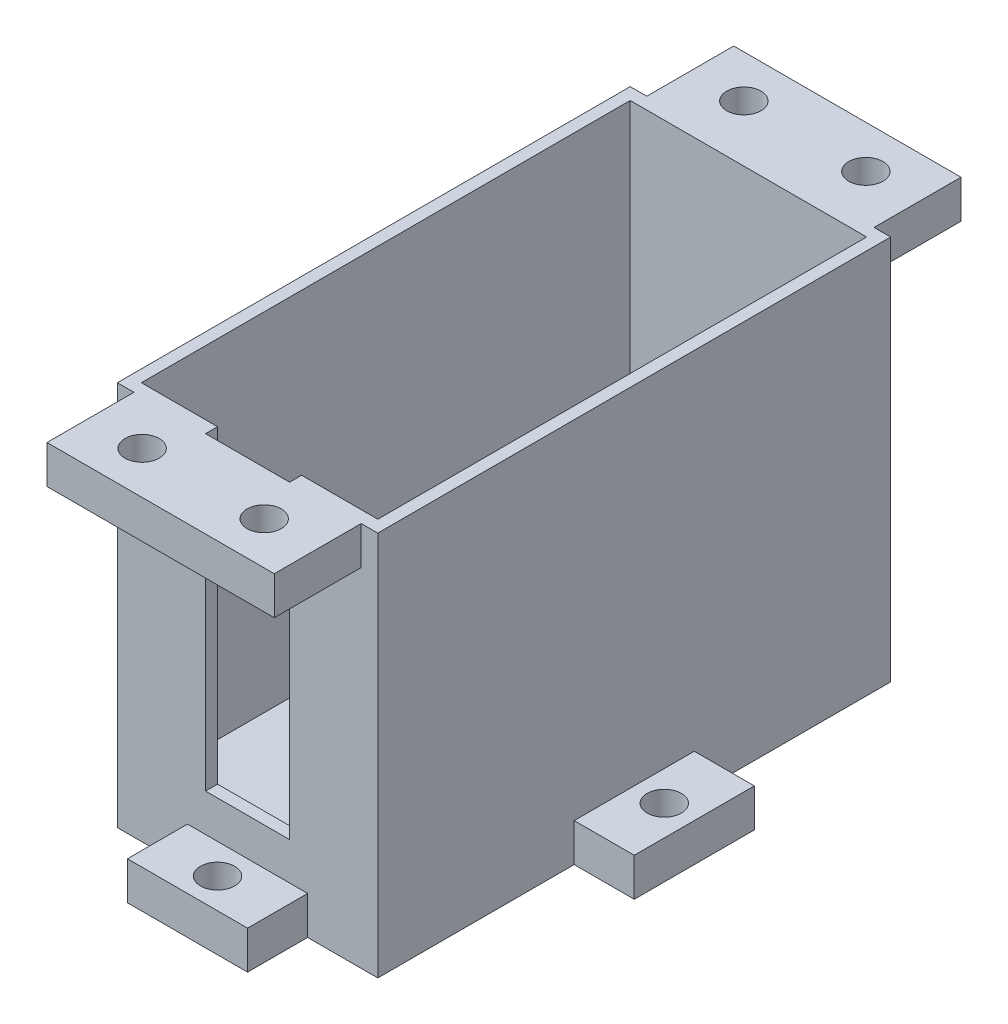
SolidWorks part; units mm, degrees
material "ABS PC"
ref_plane "Front Plane" through (0, 0, 0) normal (0, 0, 1) x (1, 0, 0)
ref_plane "Top Plane" through (0, 0, 0) normal (0, 1, 0) x (1, 0, 0)
ref_plane "Right Plane" through (0, 0, 0) normal (1, 0, 0) x (0, 0, -1)
sketch "Sketch1" plane through (0, 0, 0) normal (0, 1, 0) x (1, 0, 0)
  line L0 (0, 23.85) -> (0, -23.85) construction
  line L1 (10.8425, -21.35) -> (5, -21.35)
  line L2 (10.8425, -21.35) -> (10.8425, -5)
  line L3 (10.8425, 21.35) -> (5, 21.35)
  line L4 (-10.8425, -21.35) -> (-10.8425, -5)
  line L5 (10.8425, -21.35) -> (-10.8425, 21.35) construction
  line L6 (10.8425, 21.35) -> (-10.8425, -21.35) construction
  line L7 (5, 26.35) -> (-5, 26.35)
  line L8 (5, 26.35) -> (5, 21.35)
  line L10 (-5, 26.35) -> (-5, 21.35)
  line L11 (5, 26.35) -> (-5, 21.35) construction
  line L12 (5, 21.35) -> (-5, 26.35) construction
  line L13 (-15.8425, -5) -> (-10.8425, -5)
  line L14 (-15.8425, -5) -> (-15.8425, 5)
  line L15 (-15.8425, 5) -> (-10.8425, 5)
  line L17 (-15.8425, -5) -> (-10.8425, 5) construction
  line L18 (-15.8425, 5) -> (-10.8425, -5) construction
  line L19 (15.8425, -5) -> (10.8425, -5)
  line L20 (15.8425, -5) -> (15.8425, 5)
  line L21 (15.8425, 5) -> (10.8425, 5)
  line L23 (15.8425, -5) -> (10.8425, 5) construction
  line L24 (15.8425, 5) -> (10.8425, -5) construction
  line L25 (5, -26.35) -> (-5, -26.35)
  line L26 (5, -26.35) -> (5, -21.35)
  line L28 (-5, -26.35) -> (-5, -21.35)
  line L29 (5, -26.35) -> (-5, -21.35) construction
  line L30 (5, -21.35) -> (-5, -26.35) construction
  line L31 (-5, 21.35) -> (-10.8425, 21.35)
  line L32 (-13.3425, 0) -> (13.3425, 0) construction
  line L33 (-10.8425, 5) -> (-10.8425, 21.35)
  line L34 (-5, -21.35) -> (-10.8425, -21.35)
  line L35 (10.8425, 5) -> (10.8425, 21.35)
  circle A0 centre (0, 23.85) radius 1.425
  circle A1 centre (-13.3425, 0) radius 1.425
  circle A2 centre (13.3425, 0) radius 1.425
  circle A3 centre (0, -23.85) radius 1.425
  point P0 (0, 0)
  point P6 (0, 23.85)
  point P11 (-13.3425, 0)
  point P16 (13.3425, 0)
  point P21 (0, -23.85)
  dimension "D3" = 2.85
  dimension "D1" = 42.7
  dimension "D2" = 21.685
  dimension "D4" = 2.5
  dimension "D5" = 10
extrude "Boss-Extrude1" add sketch "Sketch1" along normal blind 3.175
sketch "Sketch2" plane through (0, 3.175, 0) normal (0, 1, 0) x (1, 0, 0)
  line L1 (10.8425, -21.35) -> (-10.8425, -21.35)
  line L2 (10.8425, -21.35) -> (10.8425, 21.35)
  line L3 (10.8425, 21.35) -> (-10.8425, 21.35)
  line L4 (-10.8425, -21.35) -> (-10.8425, 21.35)
  line L5 (10.8425, -21.35) -> (-10.8425, 21.35) construction
  line L6 (10.8425, 21.35) -> (-10.8425, -21.35) construction
  line L7 (9.8425, -20.35) -> (-9.8425, -20.35)
  line L8 (9.8425, -20.35) -> (9.8425, 20.35)
  line L9 (9.8425, 20.35) -> (-9.8425, 20.35)
  line L10 (-9.8425, -20.35) -> (-9.8425, 20.35)
  line L11 (9.8425, -20.35) -> (-9.8425, 20.35) construction
  line L12 (9.8425, 20.35) -> (-9.8425, -20.35) construction
  point P0 (0, 0)
  point P7 (0, 0)
  dimension "D1" = 1
  dimension "D2" = 1
extrude "Boss-Extrude2" add sketch "Sketch2" along normal blind 28.905
sketch "Sketch3" plane through (0, 32.08, 0) normal (0, 1, 0) x (1, 0, 0)
  line L0 (10.8425, 21.35) -> (-10.8425, 21.35) construction
  line L1 (9.4615, 28.589) -> (-9.4615, 28.589)
  line L2 (9.4615, 28.589) -> (9.4615, 21.35)
  line L3 (9.4615, 21.35) -> (-9.4615, 21.35)
  line L4 (-9.4615, 28.589) -> (-9.4615, 21.35)
  line L5 (9.4615, 28.589) -> (-9.4615, 21.35) construction
  line L6 (9.4615, 21.35) -> (-9.4615, 28.589) construction
  line L7 (-10.8425, -21.35) -> (10.8425, -21.35) construction
  line L8 (9.4615, -28.589) -> (-9.4615, -28.589)
  line L9 (9.4615, -28.589) -> (9.4615, -21.35)
  line L10 (9.4615, -21.35) -> (-9.4615, -21.35)
  line L11 (-9.4615, -28.589) -> (-9.4615, -21.35)
  line L12 (9.4615, -28.589) -> (-9.4615, -21.35) construction
  line L13 (9.4615, -21.35) -> (-9.4615, -28.589) construction
  line L14 (-5.08, 25.049) -> (5.08, 25.049) construction
  line L16 (5.08, -25.049) -> (-5.08, -25.049) construction
  circle A1 centre (-5.08, 25.049) radius 1.425
  circle A2 centre (5.08, 25.049) radius 1.425
  circle A3 centre (-5.08, -25.049) radius 1.425
  circle A4 centre (5.08, -25.049) radius 1.425
  point P0 (0, 24.9695)
  point P7 (0, -24.9695)
  point P24 (0, 25.049)
  point P26 (0, -25.049)
  dimension "D3" = 2.85
  dimension "D1" = 7.239
  dimension "D2" = 18.923
  dimension "D4" = 10.16
  dimension "D5" = 3.54
  dimension "D6" = 3.54
extrude "Boss-Extrude3" add sketch "Sketch3" against normal blind 3.175
sketch "Sketch4" plane through (0, 0, 21.35) normal (0, 0, 1) x (1, 0, 0)
  line L0 (-9.4615, 32.08) -> (9.4615, 32.08) construction
  line L1 (3.5, 32.08) -> (-3.5, 32.08)
  line L2 (3.5, 32.08) -> (3.5, 6.3072)
  line L3 (3.5, 6.3072) -> (-3.5, 6.3072)
  line L4 (-3.5, 32.08) -> (-3.5, 6.3072)
  line L5 (3.5, 32.08) -> (-3.5, 6.3072) construction
  line L6 (3.5, 6.3072) -> (-3.5, 32.08) construction
  line L7 (-5, 3.175) -> (5, 3.175) construction
  point P0 (0, 19.1936)
  dimension "D1" = 3.1322
  dimension "D2" = 7
extrude "Cut-Extrude1" cut sketch "Sketch4" against normal blind 3.175
sketch "Sketch5" plane through (0, 32.08, 0) normal (0, 1, 0) x (1, 0, 0)
  line L1 (-9.8425, 20.35) -> (-9.8425, -20.35) construction
  line L2 (9.8425, -20.35) -> (9.8425, 20.35) construction
  line L4 (-9.8425, -20.35) -> (-3.5, -20.35) construction
  circle A0 centre (0, -10.5075) radius 9.8425
sketch "Sketch6" [suppressed] plane through (0, 0, -21.35) normal (0, 0, -1) x (-1, 0, 0)
  line L1 (-9.4615, 32.08) -> (9.4615, 32.08)
  line L2 (-9.4615, 32.08) -> (-9.4615, 28.905)
  line L3 (-9.4615, 28.905) -> (9.4615, 28.905)
  line L4 (9.4615, 32.08) -> (9.4615, 28.905)
extrude "Cut-Extrude2" [suppressed] cut sketch "Sketch6" along normal blind 7.5
sketch "Sketch7" [suppressed] plane through (0, 0, -21.35) normal (0, 0, -1) x (-1, 0, 0)
  line L1 (-5, 3.175) -> (5, 3.175)
  line L2 (-5, 3.175) -> (-5, 0)
  line L3 (-5, 0) -> (5, 0)
  line L4 (5, 3.175) -> (5, 0)
extrude "Cut-Extrude3" [suppressed] cut sketch "Sketch7" along normal blind 5
sketch "Sketch8" [suppressed] plane through (0, 0, -21.35) normal (0, 0, -1) x (-1, 0, 0)
  line L1 (-10.8425, 32.08) -> (10.8425, 32.08)
  line L2 (-10.8425, 32.08) -> (-10.8425, 0)
  line L3 (-10.8425, 0) -> (10.8425, 0)
  line L4 (10.8425, 32.08) -> (10.8425, 0)
extrude "Boss-Extrude4" [suppressed] add sketch "Sketch8" along normal blind 7.5
sketch "Sketch9" [suppressed] plane through (10.8425, 0, 0) normal (1, 0, 0) x (0, 0, -1)
  line L1 (-5, 0) -> (5, 0)
  line L2 (-5, 0) -> (-5, 3.175)
  line L3 (-5, 3.175) -> (5, 3.175)
  line L4 (5, 0) -> (5, 3.175)
extrude "Cut-Extrude4" [suppressed] cut sketch "Sketch9" along normal blind 5
sketch "Sketch10" [suppressed] plane through (-10.8425, 0, 0) normal (-1, 0, 0) x (0, 0, 1)
  line L1 (-5, 3.175) -> (5, 3.175)
  line L2 (-5, 3.175) -> (-5, 0)
  line L3 (-5, 0) -> (5, 0)
  line L4 (5, 3.175) -> (5, 0)
extrude "Cut-Extrude5" [suppressed] cut sketch "Sketch10" along normal blind 5
sketch "Sketch11" [suppressed] plane through (10.8425, 0, 0) normal (1, 0, 0) x (0, 0, -1)
  line L0 (28.85, 32.08) -> (28.85, 0) construction
  line L1 (28.85, 11.04) -> (25.85, 11.04)
  line L2 (28.85, 11.04) -> (28.85, 21.04)
  line L3 (28.85, 21.04) -> (25.85, 21.04)
  line L4 (25.85, 11.04) -> (25.85, 21.04)
  line L6 (25.85, 16.04) -> (28.85, 16.04) construction
  line L7 (-21.35, 0) -> (28.85, 0) construction
  line L8 (-21.35, 32.08) -> (28.85, 32.08) construction
  dimension "D1" = 3
  dimension "D2" = 10
extrude "Boss-Extrude5" [suppressed] add sketch "Sketch11" along normal blind 5
sketch "Sketch12" [suppressed] plane through (0, 0, -25.85) normal (0, 0, 1) x (1, 0, 0)
  circle A0 centre (13.4333, 16.1011) radius 1.425
  dimension "D1" = 2.85
extrude "Cut-Extrude6" [suppressed] cut sketch "Sketch12" against normal blind 6
mirror "Mirror1" [suppressed] about plane through (0, 0, 0) normal (1, 0, 0)
sketch "Sketch13" [suppressed] plane through (-10.8425, 0, 0) normal (-1, 0, 0) x (0, 0, 1)
  line L1 (-28.85, 32.08) -> (-25.85, 32.08)
  line L2 (-28.85, 32.08) -> (-28.85, 21.04)
  line L3 (-28.85, 21.04) -> (-25.85, 21.04)
  line L4 (-25.85, 32.08) -> (-25.85, 21.04)
extrude "Boss-Extrude6" [suppressed] add sketch "Sketch13" along normal blind 5
sketch "Sketch14" [suppressed] plane through (0, 0, -25.85) normal (0, 0, 1) x (1, 0, 0)
  line L0 (-13.3425, 32.08) -> (-13.3425, 11.04) construction
  line L1 (-15.8425, 32.08) -> (-10.8425, 32.08) construction
  line L2 (-15.8425, 11.04) -> (-10.8425, 11.04) construction
  circle A0 centre (-13.3425, 27.1638) radius 1.5
  dimension "D1" = 3
extrude "Cut-Extrude7" [suppressed] cut sketch "Sketch14" against normal blind 3
mirror "Mirror2" [suppressed] about plane through (0, 0, 0) normal (1, 0, 0)
